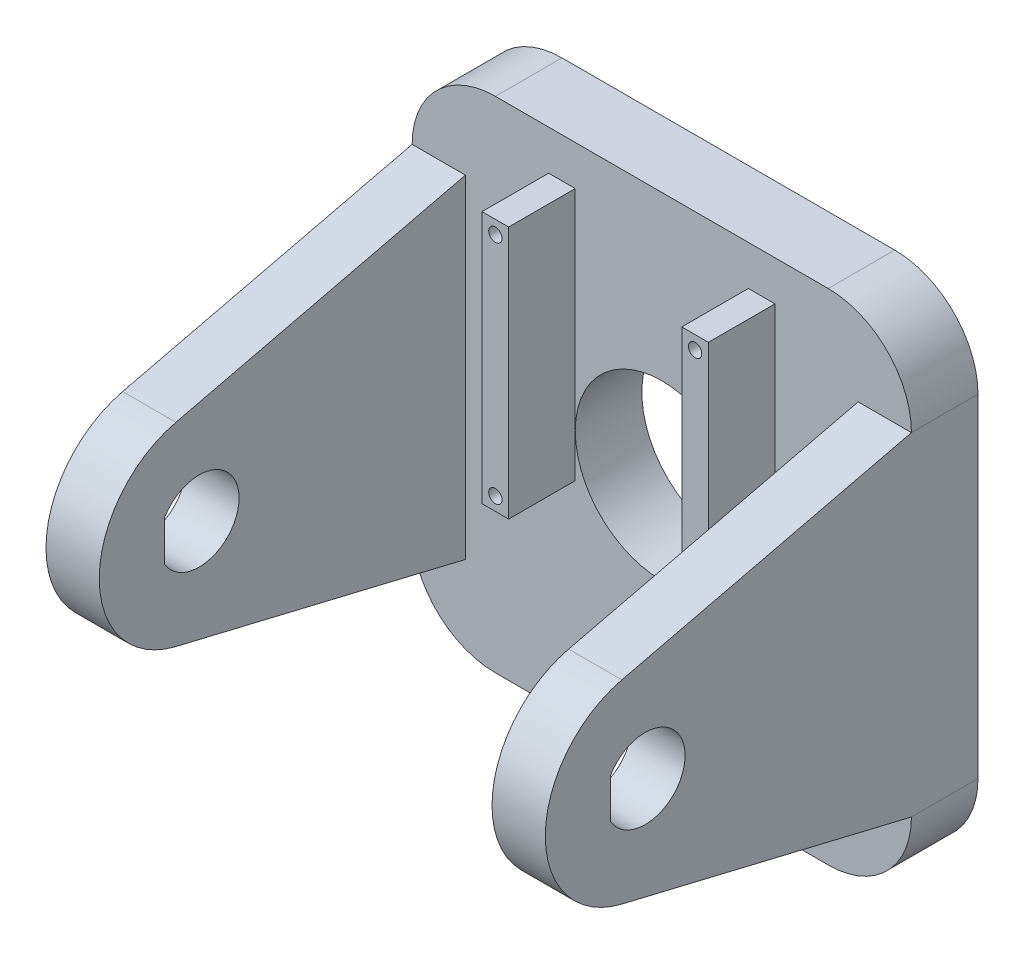
SolidWorks part; units mm, degrees
material "6061 Alloy"
ref_plane "Front Plane" through (0, 0, 0) normal (1, 0, 0) x (0, 1, 0)
ref_plane "Top Plane" through (0, 0, 0) normal (0, 0, 1) x (0, 1, 0)
ref_plane "Right Plane" through (0, 0, 0) normal (0, 1, 0) x (-1, 0, 0)
sketch "Sketch1" plane through (0, 0, 0) normal (0, 0, 1) x (0, 1, 0)
  line L1 (-25, -37.5) -> (25, -37.5)
  line L2 (-37.5, -25) -> (-37.5, 25)
  line L3 (-25, 37.5) -> (25, 37.5)
  line L4 (37.5, -25) -> (37.5, 25)
  line L5 (-37.5, -37.5) -> (37.5, 37.5) construction
  line L6 (-37.5, 37.5) -> (37.5, -37.5) construction
  arc A0 (-25, -37.5) -> (-37.5, -25) centre (-25, -25) cw
  arc A1 (25, -37.5) -> (37.5, -25) centre (25, -25) ccw
  arc A2 (25, 37.5) -> (37.5, 25) centre (25, 25) cw
  arc A3 (-37.5, 25) -> (-25, 37.5) centre (-25, 25) cw
  point P0 (0, 0)
  dimension "D2" = 12.5
  dimension "D1" = 75
extrude "Boss-Extrude1" add sketch "Sketch1" along normal blind 10
sketch "Sketch2" plane through (37.5, 0, 0) normal (1, 0, 0) x (0, 1, 0)
  line L0 (0, 50) -> (0, 0) construction
  line L1 (-25, 10) -> (25, 10) construction
  line L2 (-25, 10) -> (-14.5878, 53.4924)
  line L3 (25, 10) -> (14.5878, 53.4924)
  line L4 (25, 10) -> (25, 0) construction
  line L5 (37.5, 10) -> (25, 10) construction
  line L6 (-3, 55.1962) -> (3, 55.1962)
  circle A0 centre (0, 50) radius 15
  circle A1 centre (0, 50) radius 6
  dimension "D2" = 30
  dimension "D3" = 12
  dimension "D1" = 40
  dimension "D4" = 6
extrude "Boss-Extrude2" add sketch "Sketch2" against normal blind 8
mirror "Mirror1" about plane through (0, 0, 0) normal (1, 0, 0) of "Boss-Extrude2"
sketch "Sketch3" plane through (0, 0, 10) normal (0, 0, 1) x (1, 0, 0)
  line L0 (0, 37.5) -> (0, -37.5) construction
  line L1 (25, 37.5) -> (-25, 37.5) construction
  line L2 (-25, -37.5) -> (25, -37.5) construction
  circle A0 centre (0, 32.5) radius 1.6
  circle A1 centre (0, -32.5) radius 1.6
  dimension "D1" = 3.2
  dimension "D2" = 5
  dimension "D3" = 5
extrude "Cut-Extrude1" [suppressed] cut sketch "Sketch3" against normal through all
sketch "Sketch4" plane through (0, 0, 10) normal (0, 0, 1) x (1, 0, 0)
  circle A0 centre (0, 0) radius 13
  dimension "D1" = 26
extrude "Cut-Extrude2" cut sketch "Sketch4" against normal through all
sketch "Sketch5" plane through (0, 0, 10) normal (0, 0, 1) x (1, 0, 0)
  line L1 (-17, 31.5) -> (17, 31.5)
  line L2 (-17, 31.5) -> (-17, -6.5)
  line L3 (-17, -6.5) -> (17, -6.5)
  line L4 (17, 31.5) -> (17, -6.5)
  line L5 (-17, 31.5) -> (17, -6.5) construction
  line L6 (-17, -6.5) -> (17, 31.5) construction
  line L7 (-13, -6.5) -> (13, -6.5)
  line L8 (-13, -6.5) -> (-13, 31.5)
  line L9 (-13, 31.5) -> (13, 31.5)
  line L10 (13, -6.5) -> (13, 31.5)
  line L11 (-13, -6.5) -> (13, 31.5) construction
  line L12 (-13, 31.5) -> (13, -6.5) construction
  circle A0 centre (15, -4.5) radius 1
  circle A1 centre (-15, -4.5) radius 1
  circle A2 centre (-15, 29.5) radius 1
  circle A3 centre (15, 29.5) radius 1
  point P12 (0, 12.5)
  point P17 (0, 12.5)
  dimension "D1" = 2
  dimension "D3" = 2
  dimension "D5" = 2
  dimension "D2" = 2
  dimension "D4" = 2
  dimension "D7" = 4
extrude "Boss-Extrude3" add sketch "Sketch5" along normal blind 10 contours L3 L8 L1 L2 A2 A1 | L10 L3 L4 L1 A3 A0
